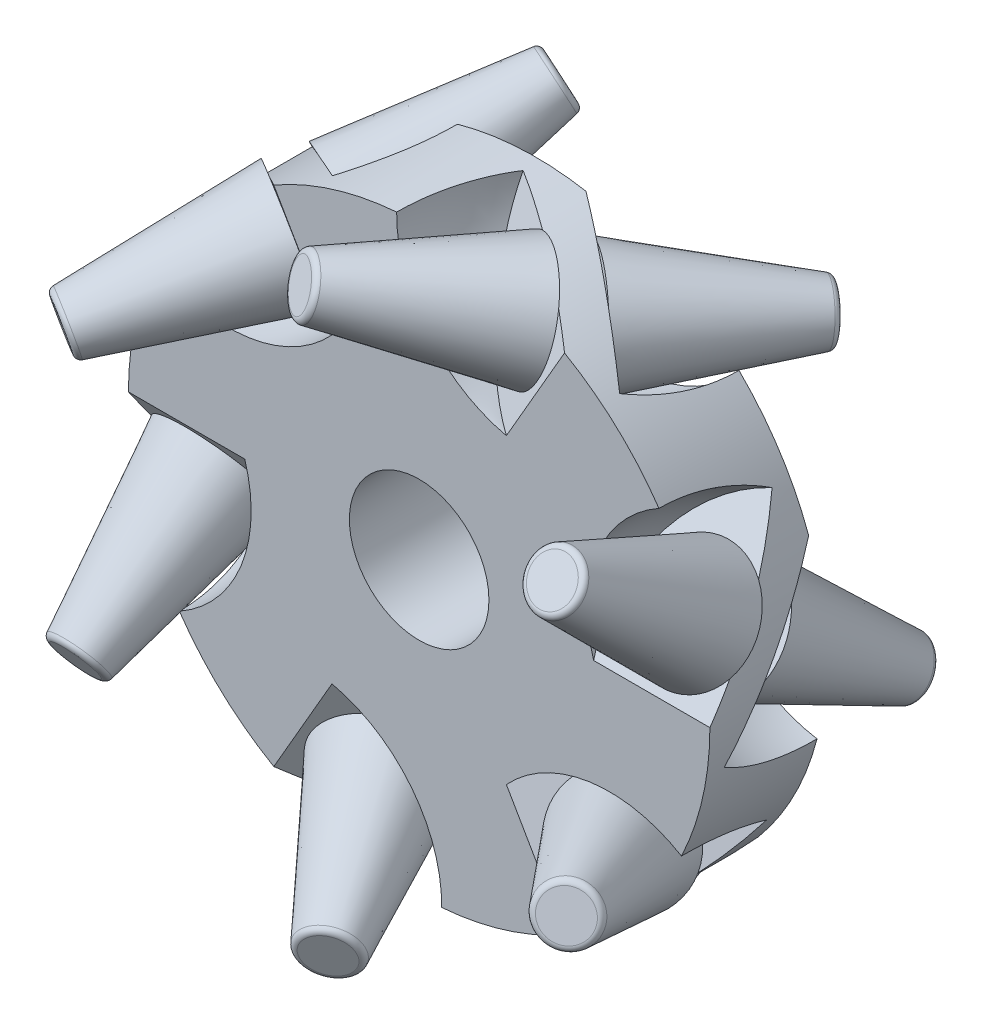
SolidWorks part; units mm, degrees
ref_plane "Front" through (0, 0, 0) normal (0, 0, 1) x (1, 0, 0)
ref_plane "Top" through (0, 0, 0) normal (0, 1, 0) x (1, 0, 0)
ref_plane "Right" through (0, 0, 0) normal (1, 0, 0) x (0, 0, -1)
sketch "Sketch1" plane through (0, 0, 0) normal (0, 0, 1) x (1, 0, 0)
  circle A0 centre (0, 0) radius 25
extrude "Boss-Extrude2" add sketch "Sketch1" against normal blind 10
sketch "Sketch3" plane through (0, 0, 0) normal (0, 0, 1) x (1, 0, 0)
  line L0 (28.0229, 0) -> (15, 0)
  arc A0 (28.0229, 0) -> (23.4851, 15.2883) centre (0, 0) ccw
  arc A2 (15, 0) -> (23.4851, 15.2883) centre (26.5062, 3.6128) cw
revolve "Cut-Revolve8" cut sketch "Sketch3" angle 35 about L0
pattern_circular "CirPattern3" count 6 over 360 about axis through (0, 0, 0) along (0, 0, 1) of "Cut-Revolve8"
sketch "Sketch8" plane through (0, 0, -10) normal (0, 0, -1) x (-1, 0, 0)
  line L1 (21.4668, 18.0128) -> (11.4907, 9.6418)
  arc A0 (21.4668, 18.0128) -> (8.1634, 26.8075) centre (0, 0) ccw
  arc A1 (11.4907, 9.6418) -> (8.1634, 26.8075) centre (17.9826, 19.8054) cw
revolve "Cut-Revolve9" cut sketch "Sketch8" angle 35 about L1
pattern_circular "CirPattern4" count 6 over 360 about axis through (0, 0, 0) along (0, 0, 1) of "Cut-Revolve9"
sketch "Sketch9" plane through (0, 0, 0) normal (0, 0, 1) x (1, 0, 0)
  circle A0 centre (0, 0) radius 6
extrude "Cut-Extrude1" cut sketch "Sketch9" against normal through all
sketch "Sketch10" plane through (0, 0, -10) normal (0, 0, -1) x (-1, 0, 0)
  circle A0 centre (0, 0) radius 6.5
extrude "Boss-Extrude3" add sketch "Sketch10" along normal blind 5 and the other way blind 1
sketch "Sketch11" plane through (0, 0, -15) normal (0, 0, -1) x (-1, 0, 0)
  circle A0 centre (0, 0) radius 1.5
extrude "Cut-Extrude2" cut sketch "Sketch11" against normal through all
sketch "Sketch12" plane through (0, 0, 0) normal (-0.4967, 0.2868, 0.8192) x (0.8679, 0.1641, 0.4688)
  circle A0 centre (7.1884, 20.0105) radius 1
extrude "Cut-Extrude3" cut sketch "Sketch12" against normal blind 5
pattern_circular "CirPattern5" count 6 over 360 about axis through (0, 0, -10) along (0, 0, 1) of "Cut-Extrude3"
sketch "Sketch14" plane through (-3.0201, -3.5992, -6.7101) normal (-0.3687, -0.4394, -0.8192) x (-0.9296, 0.1743, 0.3249)
  circle A0 centre (-16.4018, -11.5201) radius 5
extrude "Boss-Extrude4" add sketch "Sketch14" along normal blind 15 draft 10
sketch "Sketch15" plane through (0, 0, 0) normal (0.4967, 0.2868, 0.8192) x (0.8679, -0.1641, -0.4688)
  circle A0 centre (16.4287, -13.4978) radius 5
extrude "Boss-Extrude5" add sketch "Sketch15" along normal blind 15 draft 10
fillet "Fillet1" radius 0.5 1 edges at (23.7233, -11.1343, 7.824)
fillet "Fillet2" radius 0.5 1 edges at (6.6959, -21.1249, -19.9941)
pattern_circular "CirPattern13" count 6 over 360 about axis through (0, 0, 0) along (0, 0, 1) of "Boss-Extrude4"
pattern_circular "CirPattern14" count 6 over 360 about axis through (0, 0, 0) along (0, 0, 1) of "Boss-Extrude5"
fillet "Fillet3" radius 0.5 5 edges at (3.2259, -24.3682, 7.824) (-20.4974, -15.163, 7.6944) (-19.6958, 11.1343, 10.2663) (0.8016, 24.3682, 10.2663) (20.4974, 11.3047, 10.396)
fillet "Fillet4" radius 0.5 5 edges at (23.44, -3.8339, -20.1754) (14.8053, 17.399, -20.2179) (-6.6959, 25.2757, -17.7677) (-23.44, 7.7688, -17.5864) (-18.6829, -17.399, -17.544)
